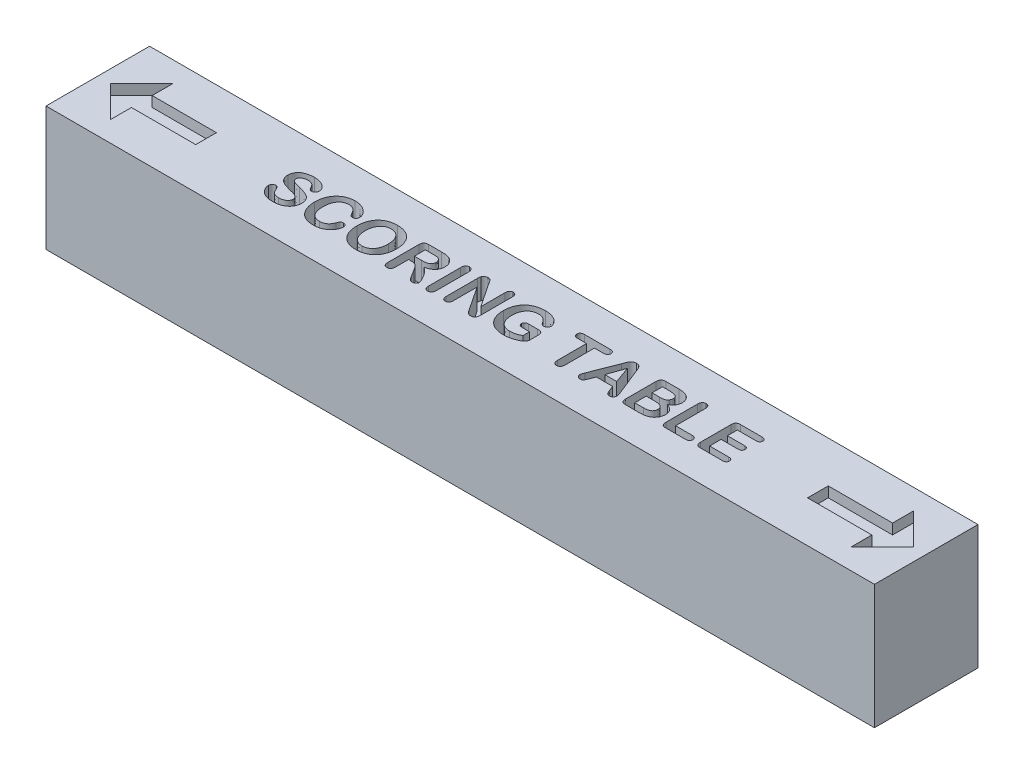
SolidWorks part; units mm, degrees
ref_plane "Front Plane" through (0, 0, 0) normal (0, 0, 1) x (1, 0, 0)
ref_plane "Top Plane" through (0, 0, 0) normal (0, 1, 0) x (1, 0, 0)
ref_plane "Right Plane" through (0, 0, 0) normal (1, 0, 0) x (0, 0, -1)
sketch "Sketch1" plane through (0, 0, 0) normal (0, 1, 0) x (1, 0, 0)
  line L1 (3048, 381) -> (-3048, 381)
  line L2 (3048, 381) -> (3048, -381)
  line L3 (3048, -381) -> (-3048, -381)
  line L4 (-3048, 381) -> (-3048, -381)
  line L5 (3048, 381) -> (-3048, -381) construction
  line L6 (3048, -381) -> (-3048, 381) construction
  point P0 (0, 0)
  dimension "D1" = 6096
  dimension "D2" = 762
extrude "Boss-Extrude1" add sketch "Sketch1" along normal blind 914.4
sketch "Sketch2" plane through (0, 914.4, 0) normal (0, 1, 0) x (1, 0, 0)
  line L0 (-3048, -152.4) -> (3048, -152.4) construction
  line L3 (-3048, 381) -> (-3048, -381) construction
  line L4 (3048, -381) -> (3048, 381) construction
  line L5 (-3048, -381) -> (3048, -381) construction
  text T0 "SCORING TABLE" font "Arial Rounded MT Bold" height in points 1200
  dimension "D1" = 228.6
extrude "Cut-Extrude1" cut sketch "Sketch2" against normal blind 152.4
sketch "Sketch3" plane through (0, 914.4, 0) normal (0, 1, 0) x (1, 0, 0)
  line L0 (2724.15, 76.2) -> (2724.15, 231.775)
  line L1 (2251.075, 76.2) -> (2724.15, 76.2)
  line L2 (2251.075, 76.2) -> (2251.075, -76.2)
  line L3 (2251.075, -76.2) -> (2724.15, -76.2)
  line L4 (2724.15, 76.2) -> (2724.15, -76.2) construction
  line L5 (2724.15, 231.775) -> (2955.925, 0)
  line L6 (2955.925, 0) -> (2724.15, -231.775)
  line L7 (2724.15, -231.775) -> (2724.15, -76.2)
  line L8 (3048, -381) -> (3048, 381) construction
  point P7 (2724.15, 0)
  point P10 (3048, 0)
  point P11 (2421.3598, -24.671)
  dimension "D1" = 704.85
  dimension "D2" = 473.075
  dimension "D3" = 152.4
  dimension "D4" = 92.075
extrude "Cut-Extrude2" cut sketch "Sketch3" against normal blind 76.2
mirror "Mirror1" about plane through (0, 0, 0) normal (1, 0, 0) of "Cut-Extrude2"
